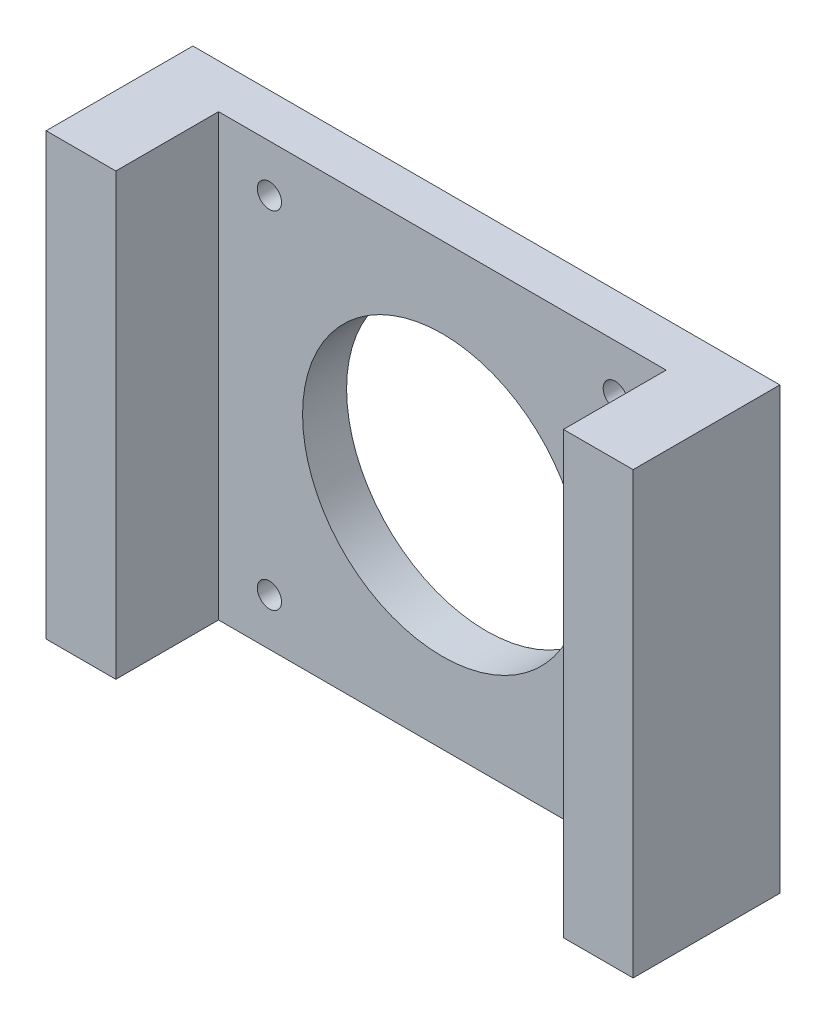
SolidWorks part; units mm, degrees
material "6061 合金"
ref_plane "前基準面" through (0, 0, 0) normal (0, 0, 1) x (1, 0, 0)
ref_plane "上基準面" through (0, 0, 0) normal (0, 1, 0) x (1, 0, 0)
ref_plane "右基準面" through (0, 0, 0) normal (1, 0, 0) x (0, 0, -1)
sketch "草圖1" plane through (0, 0, 0) normal (0, 0, 1) x (1, 0, 0)
  line L1 (-40, -30) -> (40, -30)
  line L2 (-40, -30) -> (-40, 30)
  line L3 (-40, 30) -> (40, 30)
  line L4 (40, -30) -> (40, 30)
  line L5 (-40, -30) -> (40, 30) construction
  line L6 (-40, 30) -> (40, -30) construction
  point P0 (0, 0)
  dimension "D1" = 60
  dimension "D2" = 80
extrude "填料-伸長1" add sketch "草圖1" along normal blind 20
sketch "草圖2" plane through (0, 0, 20) normal (0, 0, 1) x (1, 0, 0)
  line L0 (40, 30) -> (-40, 30) construction
  line L1 (-30.5, -30) -> (30.5, -30)
  line L2 (-30.5, -30) -> (-30.5, 30)
  line L3 (-30.5, 30) -> (30.5, 30)
  line L4 (30.5, -30) -> (30.5, 30)
  line L5 (-30.5, -30) -> (30.5, 30) construction
  line L6 (-30.5, 30) -> (30.5, -30) construction
  point P0 (0, 0)
  dimension "D1" = 61
extrude "除料-伸長1" cut sketch "草圖2" against normal offset from surface (14 mm away) 6 up to face at (0, 0, 0)
sketch "草圖3" plane through (0, 0, 0) normal (0, 0, -1) x (-1, 0, 0)
  circle A0 centre (0, 0) radius 19.05
  dimension "D1" = 38.1
extrude "除料-伸長2" cut sketch "草圖3" against normal through all
hole_wizard "M4x0.7 螺紋孔1" positions "草圖4" profile "草圖6" tap size "M4x0.7" standard "Ansi Metric" end condition through all
sketch "草圖4" plane through (0, 0, 0) normal (0, 0, -1) x (-1, 0, 0)
  line L3 (-23.57, -23.57) -> (23.57, -23.57) construction
  line L4 (-23.57, -23.57) -> (-23.57, 23.57) construction
  line L5 (-23.57, 23.57) -> (23.57, 23.57) construction
  line L6 (23.57, -23.57) -> (23.57, 23.57) construction
  line L7 (-23.57, -23.57) -> (23.57, 23.57) construction
  line L8 (-23.57, 23.57) -> (23.57, -23.57) construction
  point P120 (23.57, 23.57)
  point P201 (-23.57, -23.57)
  point P202 (-23.57, 23.57)
  point P203 (23.57, -23.57)
  dimension "D1" = 47.14
  dimension "D2" = 47.14
sketch "草圖6" plane through (-23.57, 23.57, 0) normal (1, 0, 0) x (0, 1, 0)
  line L0 (0, 0) -> (0, 20)
  line L1 (0, 20) -> (1.65, 20)
  line L2 (1.65, 20) -> (1.65, 0)
  line L5 (1.65, 0) -> (0, 0)
  line L11 (0, -6.35) -> (0, 107.95) construction
  dimension "貫穿螺孔鑽直徑" = 3.3
  dimension "貫穿螺孔鑽深度" = 20
